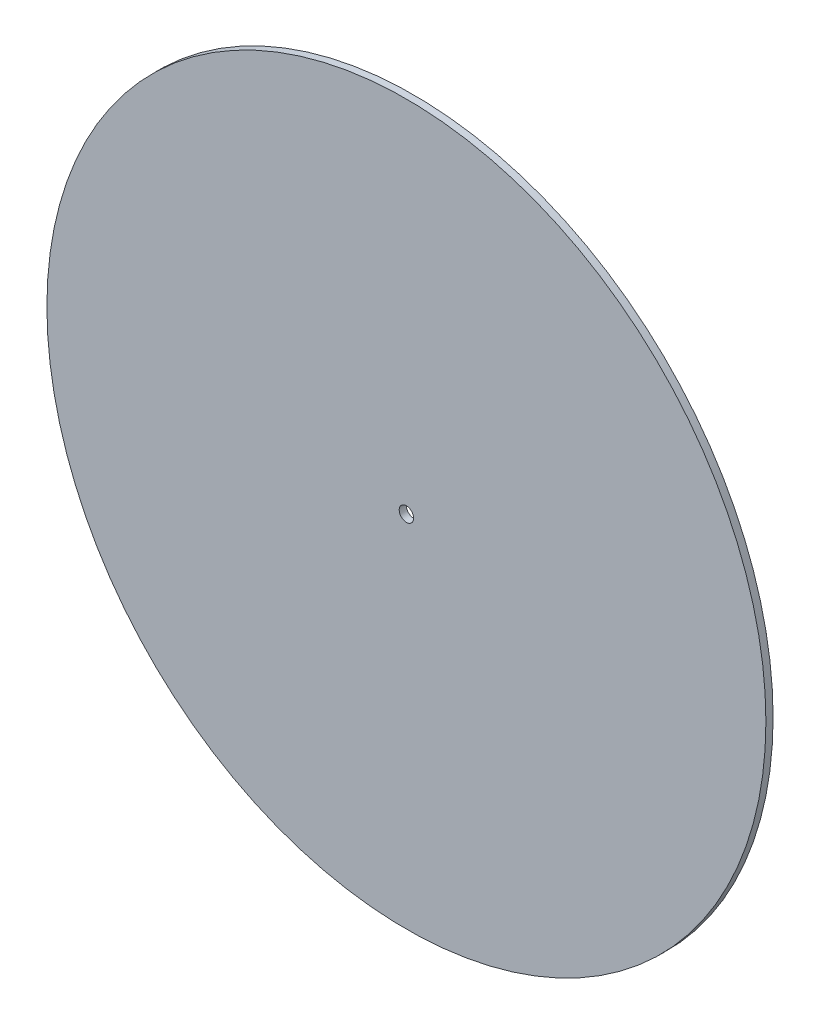
SolidWorks part; units mm, degrees
ref_plane "Front Plane" through (0, 0, 0) normal (0, 0, 1) x (1, 0, 0)
ref_plane "Top Plane" through (0, 0, 0) normal (0, 1, 0) x (1, 0, 0)
ref_plane "Right Plane" through (0, 0, 0) normal (1, 0, 0) x (0, 0, -1)
sketch "Sketch1" plane through (0, 0, 0) normal (0, 0, 1) x (1, 0, 0)
  circle A0 centre (0, 0) radius 100
  circle A1 centre (0, 0) radius 2
  dimension "D1" = 200
  dimension "D2" = 4
extrude "Boss-Extrude1" add sketch "Sketch1" along normal blind 2
